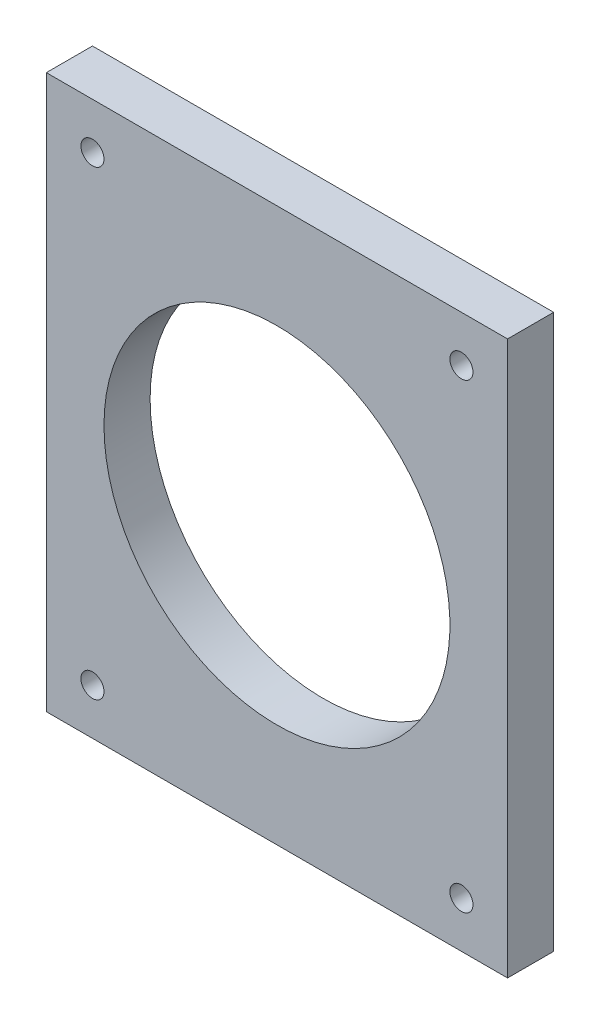
SolidWorks part; units mm, degrees
ref_plane "Front Plane" through (0, 0, 0) normal (0, 0, 1) x (1, 0, 0)
ref_plane "Top Plane" through (0, 0, 0) normal (0, 1, 0) x (1, 0, 0)
ref_plane "Right Plane" through (0, 0, 0) normal (1, 0, 0) x (0, 0, -1)
sketch "Sketch1" plane through (0, 0, 0) normal (0, 0, 1) x (1, 0, 0)
  line L1 (63.5, -76.2) -> (-63.5, -76.2)
  line L2 (63.5, -76.2) -> (63.5, 76.2)
  line L3 (63.5, 76.2) -> (-63.5, 76.2)
  line L4 (-63.5, -76.2) -> (-63.5, 76.2)
  line L5 (63.5, -76.2) -> (-63.5, 76.2) construction
  line L6 (63.5, 76.2) -> (-63.5, -76.2) construction
  point P0 (0, 0)
  dimension "D1" = 127
  dimension "D2" = 152.4
extrude "Boss-Extrude1" add sketch "Sketch1" along normal blind 12.7
sketch "Sketch2" plane through (0, 0, 0) normal (0, 0, -1) x (-1, 0, 0)
  circle A0 centre (0, 0) radius 47.625
  dimension "D1" = 95.25
extrude "Cut-Extrude1" cut sketch "Sketch2" against normal through all
sketch "Sketch3" plane through (0, 0, 0) normal (0, 0, -1) x (-1, 0, 0)
  circle A0 centre (-50.8, 63.5) radius 3.175
  circle A1 centre (50.8, 63.5) radius 3.175
  circle A2 centre (50.8, -63.5) radius 3.175
  circle A3 centre (-50.8, -63.5) radius 3.175
  dimension "D1" = 6.35
extrude "Cut-Extrude3" cut sketch "Sketch3" against normal through all both and the other way through all
